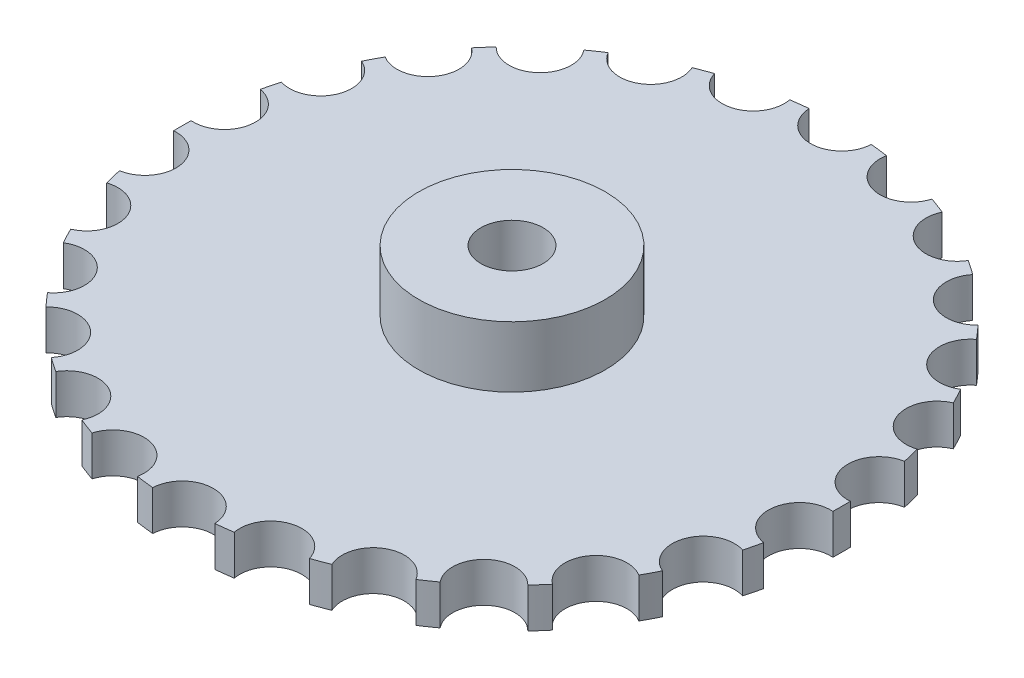
SolidWorks part; units mm, degrees
ref_plane "Front Plane" through (0, 0, 0) normal (0, 0, 1) x (1, 0, 0)
ref_plane "Top Plane" through (0, 0, 0) normal (0, 1, 0) x (1, 0, 0)
ref_plane "Right Plane" through (0, 0, 0) normal (1, 0, 0) x (0, 0, -1)
sketch "Sketch1" plane through (0, 0, 0) normal (0, 1, 0) x (1, 0, 0)
  line L0 (0, 0) -> (0, 26.5) construction
  line L1 (0, 0) -> (6.3419, 25.73) construction
  circle A1 centre (0, 26.5) radius 2.5
  circle A2 centre (6.3419, 25.73) radius 2.5
  circle A3 centre (12.3152, 23.4646) radius 2.5
  circle A4 centre (17.5728, 19.8355) radius 2.5
  circle A5 centre (21.8091, 15.0537) radius 2.5
  circle A6 centre (24.7779, 9.397) radius 2.5
  circle A7 centre (26.3068, 3.1942) radius 2.5
  circle A8 centre (26.3068, -3.1942) radius 2.5
  circle A9 centre (24.7779, -9.397) radius 2.5
  circle A10 centre (21.8091, -15.0537) radius 2.5
  circle A11 centre (17.5728, -19.8355) radius 2.5
  circle A12 centre (12.3152, -23.4646) radius 2.5
  circle A13 centre (6.3419, -25.73) radius 2.5
  circle A14 centre (0, -26.5) radius 2.5
  circle A15 centre (-6.3419, -25.73) radius 2.5
  circle A16 centre (-12.3152, -23.4646) radius 2.5
  circle A17 centre (-17.5728, -19.8355) radius 2.5
  circle A18 centre (-21.8091, -15.0537) radius 2.5
  circle A19 centre (-24.7779, -9.397) radius 2.5
  circle A20 centre (-26.3068, -3.1942) radius 2.5
  circle A21 centre (-26.3068, 3.1942) radius 2.5
  circle A22 centre (-24.7779, 9.397) radius 2.5
  circle A23 centre (-21.8091, 15.0537) radius 2.5
  circle A24 centre (-17.5728, 19.8355) radius 2.5
  circle A25 centre (-12.3152, 23.4646) radius 2.5
  circle A26 centre (-6.3419, 25.73) radius 2.5
  dimension "D2" = 5
  dimension "D4" = 13.846
  dimension "D3" = 26
sketch "Sketch2" plane through (0, 0, 0) normal (0, 1, 0) x (1, 0, 0)
  circle A0 centre (0, 0) radius 26.5
extrude "Boss-Extrude1" add sketch "Sketch2" along normal mid plane 3.2 contours A0
extrude "Cut-Extrude2" cut sketch "Sketch1" against normal through all both and the other way through all
sketch "Sketch3" plane through (0, 0, 0) normal (0, 1, 0) x (1, 0, 0)
  circle A0 centre (0, 0) radius 7.5
  dimension "D1" = 15
extrude "Boss-Extrude2" add sketch "Sketch3" along normal mid plane 13
hole_wizard "Ø5.0mm Dowel Hole2" positions "Sketch6" profile "Sketch7" hole size "Ø5.0" standard "ANSI Metric" end condition through all
sketch "Sketch6" plane through (0, 6.5, 0) normal (0, 1, 0) x (1, 0, 0)
  point P0 (0, 0)
sketch "Sketch7" plane through (0, 6.5, 0) normal (1, 0, 0) x (0, 0, 1)
  line L0 (0, 0) -> (0, 13)
  line L1 (0, 13) -> (2.5, 13)
  line L2 (2.5, 13) -> (2.5, 0)
  line L5 (2.5, 0) -> (0, 0)
  line L11 (0, -6.35) -> (0, 107.95) construction
  dimension "Thru Hole Dia." = 5
  dimension "Thru Hole Depth" = 13
ref_plane "Plane1" through (0, 0, 0) normal (0, -1, 0) x (-1, 0, 0)
